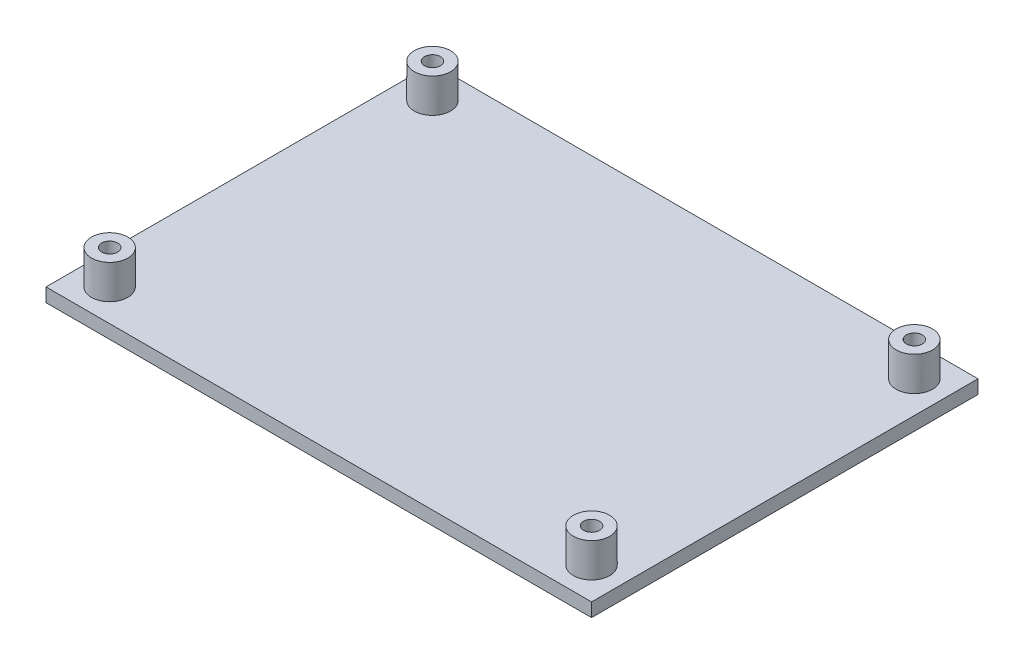
SolidWorks part; units mm, degrees
ref_plane "Front" through (0, 0, 0) normal (0, 0, 1) x (1, 0, 0)
ref_plane "Top" through (0, 0, 0) normal (0, 1, 0) x (1, 0, 0)
ref_plane "Right" through (0, 0, 0) normal (1, 0, 0) x (0, 0, -1)
sketch "Sketch1" plane through (0, 0, 0) normal (0, 1, 0) x (1, 0, 0)
  line L1 (0, 0) -> (120, 0)
  line L2 (0, 0) -> (0, 85)
  line L3 (0, 85) -> (120, 85)
  line L4 (120, 0) -> (120, 85)
extrude "Boss-Extrude1" add sketch "Sketch1" along normal blind 3
sketch "Sketch2" plane through (0, 3, 0) normal (0, 1, 0) x (1, 0, 0)
  line L0 (120, 85) -> (0, 85) construction
  line L1 (0, 85) -> (0, 0) construction
  line L2 (0, 0) -> (120, 0) construction
  line L3 (120, 0) -> (120, 85) construction
  circle A0 centre (7, 78) radius 1.75
  circle A1 centre (7, 78) radius 4
  circle A2 centre (7, 7) radius 1.75
  circle A3 centre (7, 7) radius 4
  circle A4 centre (113, 7) radius 1.75
  circle A5 centre (113, 7) radius 4
  circle A6 centre (113, 78) radius 1.75
  circle A7 centre (113, 78) radius 4
  dimension "D1" = 7
  dimension "D3" = 7
  dimension "D5" = 7
  dimension "D2" = 7
  dimension "D4" = 7
  dimension "D6" = 7
  dimension "D7" = 7
  dimension "D8" = 7
extrude "Boss-Extrude2" add sketch "Sketch2" along normal blind 7.5
